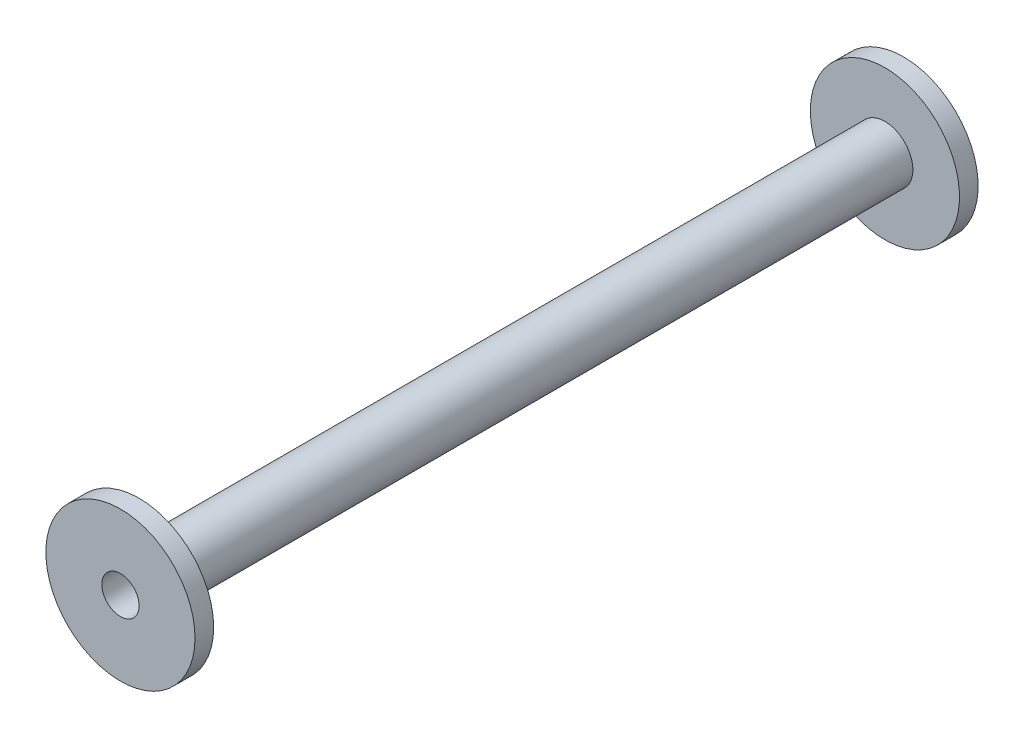
SolidWorks part; units mm, degrees
material "ABS PC"
ref_plane "Front Plane" through (0, 0, 0) normal (0, 0, 1) x (1, 0, 0)
ref_plane "Top Plane" through (0, 0, 0) normal (0, 1, 0) x (1, 0, 0)
ref_plane "Right Plane" through (0, 0, 0) normal (1, 0, 0) x (0, 0, -1)
sketch "Sketch1" plane through (0, 0, 0) normal (0, 0, 1) x (1, 0, 0)
  circle A0 centre (0, 0) radius 12.7
  circle A1 centre (0, 0) radius 19.05
  dimension "D1" = 25.4
  dimension "D2" = 38.1
extrude "Boss-Extrude1" add sketch "Sketch1" along normal mid plane 533.4
sketch "Sketch2" plane through (0, 0, 266.7) normal (0, 0, 1) x (1, 0, 0)
  circle A0 centre (0, 0) radius 50.8
  circle A1 centre (0, 0) radius 12.7 construction
  circle A2 centre (0, 0) radius 12.7
  dimension "D1" = 101.6
extrude "Boss-Extrude2" add sketch "Sketch2" against normal blind 12.7
sketch "Sketch3" plane through (0, 0, -266.7) normal (0, 0, -1) x (-1, 0, 0)
  circle A0 centre (0, 0) radius 12.7 construction
  circle A1 centre (0, 0) radius 12.7
  circle A2 centre (0, 0) radius 50.8
  dimension "D1" = 101.6
extrude "Boss-Extrude3" add sketch "Sketch3" against normal blind 12.7
